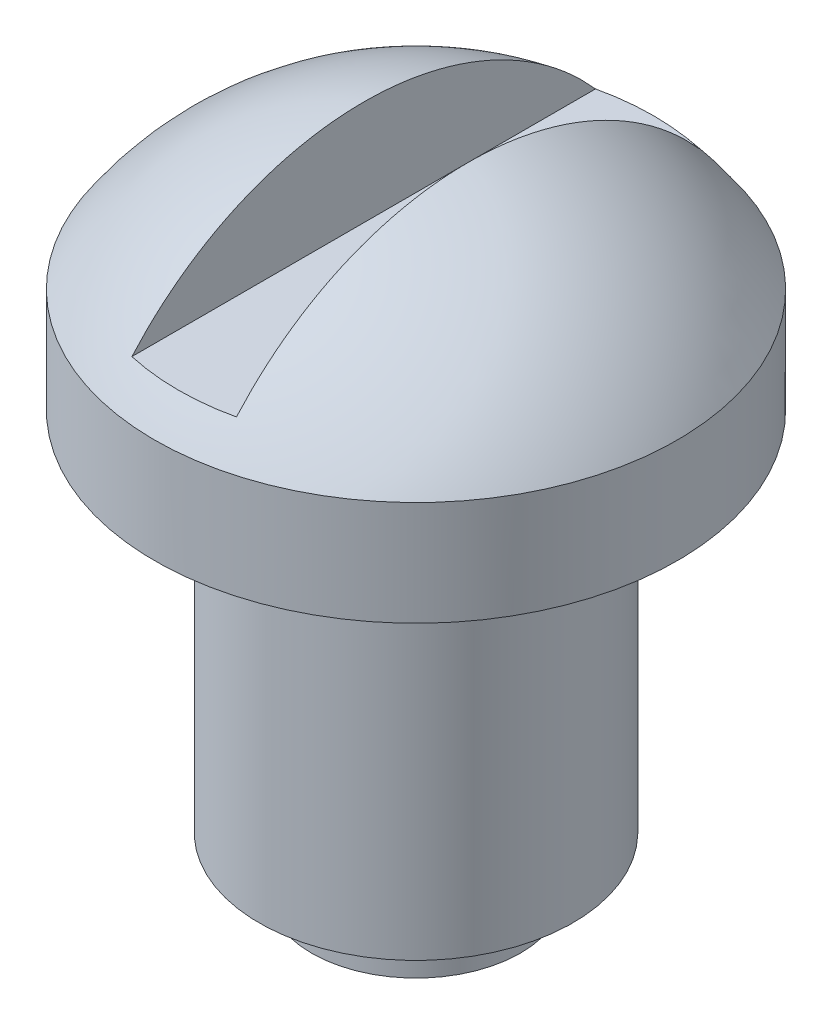
SolidWorks part; units mm, degrees
ref_plane "Front Plane" through (0, 0, 0) normal (0, 0, 1) x (1, 0, 0)
ref_plane "Top Plane" through (0, 0, 0) normal (0, 1, 0) x (1, 0, 0)
ref_plane "Right Plane" through (0, 0, 0) normal (1, 0, 0) x (0, 0, -1)
sketch "Sketch1" plane through (0, 0, 0) normal (0, 0, 1) x (1, 0, 0)
  line L0 (0, 10) -> (0, 12.6834)
  line L1 (0, 0) -> (2, 0)
  line L2 (0, 0) -> (0, 1)
  line L3 (0, 1) -> (2, 1)
  line L4 (2, 0) -> (2, 1)
  line L5 (0, 1) -> (3, 1)
  line L6 (0, 1) -> (0, 8)
  line L7 (0, 8) -> (3, 8)
  line L8 (3, 1) -> (3, 8)
  line L9 (0, 8) -> (5, 8)
  line L10 (0, 8) -> (0, 10)
  line L11 (0, 10) -> (5, 10)
  line L12 (5, 8) -> (5, 10)
  arc A0 (5, 10) -> (0, 12.6834) centre (0, 6.6834) ccw
  dimension "D7" = 6
  dimension "D1" = 2
  dimension "D2" = 1
  dimension "D3" = 7
  dimension "D4" = 3
  dimension "D5" = 5
  dimension "D6" = 2
revolve "Revolve1" add sketch "Sketch1" angle 360 about L10
sketch "Sketch2" plane through (0, 0, 0) normal (0, 0, 1) x (1, 0, 0)
  line L0 (5, 10) -> (-5, 10) construction
  line L1 (5, 10) -> (-5, 10)
  line L2 (0, 10) -> (0, 12.6834) construction
  line L3 (1, 10.5995) -> (-1, 10.5995)
  line L4 (-1, 10.5995) -> (-1, 12.5995)
  line L5 (1, 10.5995) -> (1, 12.5995)
  arc A0 (5, 10) -> (-5, 10) centre (0, 6.6834) ccw construction
  arc A1 (5, 10) -> (-5, 10) centre (0, 6.6834) ccw
  dimension "D1" = 2
  dimension "D2" = 2
extrude "Cut-Extrude1" cut sketch "Sketch2" against normal through all both and the other way through all contours L2 L3 L5 A1 | L3 L2 A1 L4
